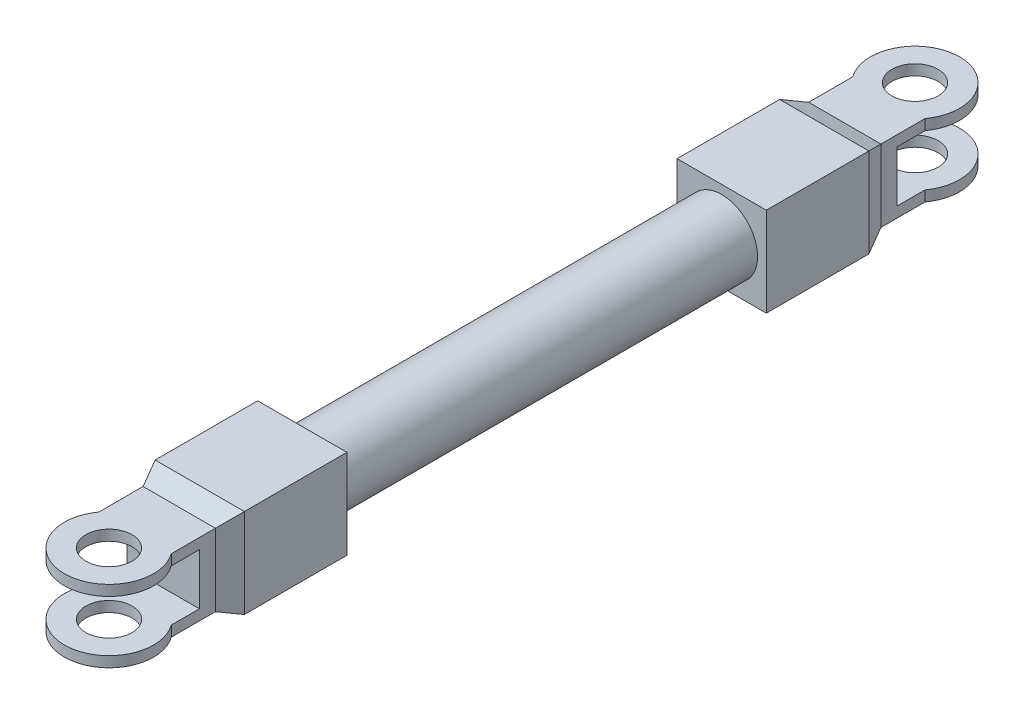
SolidWorks part; units mm, degrees
ref_plane "Front Plane" through (0, 0, 0) normal (0, 0, 1) x (1, 0, 0)
ref_plane "Top Plane" through (0, 0, 0) normal (0, 1, 0) x (1, 0, 0)
ref_plane "Right Plane" through (0, 0, 0) normal (1, 0, 0) x (0, 0, -1)
sketch "Sketch2" plane through (0, 0, 0) normal (0, 0, 1) x (1, 0, 0)
  circle A0 centre (0, 0) radius 70
  dimension "D1" = 140
extrude "Boss-Extrude2" add sketch "Sketch2" against normal blind 1018
sketch "Sketch4" plane through (0, 0, 0) normal (0, 0, 1) x (1, 0, 0)
  line L1 (-87, 87) -> (87, 87)
  line L2 (-87, 87) -> (-87, -87)
  line L3 (-87, -87) -> (87, -87)
  line L4 (87, 87) -> (87, -87)
  line L5 (-87, 87) -> (87, -87) construction
  line L6 (-87, -87) -> (87, 87) construction
  point P0 (0, 0)
  dimension "D1" = 174
  dimension "D2" = 174
extrude "Boss-Extrude3" add sketch "Sketch4" against normal mid plane 200
sketch "Sketch7" plane through (0, 0, -1018) normal (0, 0, -1) x (-1, 0, 0)
  line L1 (-87, 87) -> (87, 87)
  line L2 (-87, 87) -> (-87, -87)
  line L3 (-87, -87) -> (87, -87)
  line L4 (87, 87) -> (87, -87)
  line L5 (-87, 87) -> (87, -87) construction
  line L6 (-87, -87) -> (87, 87) construction
  point P0 (0, 0)
  dimension "D1" = 174
  dimension "D2" = 174
extrude "Boss-Extrude4" add sketch "Sketch7" against normal mid plane 200
ref_plane "Plane1" through (0, 0, 140) normal (0, 0, 1) x (1, 0, 0)
sketch "Sketch8" plane through (0, 0, 140) normal (0, 0, 1) x (1, 0, 0)
  line L1 (-70.5, 70.5) -> (70.5, 70.5)
  line L2 (-70.5, 70.5) -> (-70.5, -70.5)
  line L3 (-70.5, -70.5) -> (70.5, -70.5)
  line L4 (70.5, 70.5) -> (70.5, -70.5)
  line L5 (-70.5, 70.5) -> (70.5, -70.5) construction
  line L6 (-70.5, -70.5) -> (70.5, 70.5) construction
  point P0 (0, 0)
  dimension "D1" = 141
  dimension "D2" = 141
loft "Loft1" add profiles "Sketch8" section face at (0, 0, 100) section "Sketch8"
ref_plane "Plane2" through (0, 0, -160) normal (0, 0, -1) x (-1, 0, 0)
sketch "Sketch9" plane through (0, 0, -160) normal (0, 0, -1) x (-1, 0, 0)
  line L5 (-71.5, 71.5) -> (71.5, 71.5)
  line L6 (-71.5, 71.5) -> (-71.5, -71.5)
  line L7 (-71.5, -71.5) -> (71.5, -71.5)
  line L8 (71.5, 71.5) -> (71.5, -71.5)
  line L9 (-71.5, 71.5) -> (71.5, -71.5) construction
  line L10 (-71.5, -71.5) -> (71.5, 71.5) construction
  point P0 (0, 0)
  point P1 (0, 0)
  dimension "D1" = 143
  dimension "D2" = 143
ref_plane "Plane3" through (0, 0, -1158) normal (0, 0, -1) x (-1, 0, 0)
sketch "Sketch10" plane through (0, 0, -1158) normal (0, 0, -1) x (-1, 0, 0)
  line L0 (-71.5, 71.5) -> (71.5, -71.5) construction
  line L1 (-70.5, 70.5) -> (70.5, 70.5)
  line L2 (-70.5, 70.5) -> (-70.5, -70.5)
  line L3 (-70.5, -70.5) -> (70.5, -70.5)
  line L4 (70.5, 70.5) -> (70.5, -70.5)
  line L5 (-70.5, 70.5) -> (70.5, -70.5) construction
  line L6 (-70.5, -70.5) -> (70.5, 70.5) construction
  point P0 (0, 0)
  dimension "D1" = 141
  dimension "D2" = 141
loft "Loft8" add profiles "Sketch10" section face at (0, 0, -1118) section "Sketch10"
ref_plane "Plane4" through (0, 70.5, 0) normal (0, 1, 0) x (-1, 0, 0)
sketch "Sketch14" plane through (0, 70.5, 0) normal (0, 1, 0) x (-1, 0, 0)
  line L0 (94.8419, 140) -> (-94.8419, 140) construction
  circle A0 centre (0, 277) radius 87
  dimension "D1" = 174
  dimension "D2" = 137
extrude "Boss-Extrude5" add sketch "Sketch14" against normal blind 141 separate body contours A0
sketch "Sketch16" plane through (0, 70.5, 0) normal (0, 1, 0) x (1, 0, 0)
  circle A0 centre (0, -277) radius 45
  dimension "D1" = 90
extrude "Cut-Extrude1" cut sketch "Sketch16" against normal up to next (141 mm away)
sketch "Sketch17" plane through (0, 0, 140) normal (0, 0, 1) x (1, 0, 0)
  line L1 (-70.5, 70.5) -> (70.5, 70.5)
  line L2 (-70.5, 70.5) -> (-70.5, -70.5)
  line L3 (-70.5, -70.5) -> (70.5, -70.5)
  line L4 (70.5, 70.5) -> (70.5, -70.5)
  line L5 (-70.5, 70.5) -> (70.5, -70.5) construction
  line L6 (-70.5, -70.5) -> (70.5, 70.5) construction
  point P0 (0, 0)
  dimension "D1" = 141
  dimension "D2" = 141
extrude "Boss-Extrude6" add sketch "Sketch17" along normal up to next
ref_plane "Plane6" through (-94.5, 0, 0) normal (-1, 0, 0) x (0, 0, 1)
sketch "Sketch23" plane through (-94.5, 0, 0) normal (-1, 0, 0) x (0, 0, 1)
  line L0 (226.0221, -70.5) -> (364, -70.5) construction
  line L1 (171.1765, -50) -> (367.3984, -50)
  line L2 (171.1765, -50) -> (171.1765, 50)
  line L3 (171.1765, 50) -> (367.3984, 50)
  line L4 (367.3984, -50) -> (367.3984, 50)
  dimension "D1" = 100
  dimension "D2" = 20.5
extrude "Cut-Extrude2" cut sketch "Sketch23" against normal blind 201
sketch "Sketch24" plane through (0, 0, 0) normal (0, 1, 0) x (1, 0, 0)
  line L0 (-70.5, 1158) -> (70.5, 1158) construction
  line L2 (-70.5, 1158) -> (70.5, 1158)
  line L3 (-70.5, 1158) -> (-70.5, 1244.0221)
  line L5 (70.5, 1158) -> (70.5, 1244.0221)
  arc A0 (70.5, 1244.0221) -> (-70.5, 1244.0221) centre (0, 1295) ccw
  point P4 (0, 1158)
  dimension "D1" = 174
  dimension "D2" = 137
  dimension "D3" = 141
extrude "Boss-Extrude7" add sketch "Sketch24" along normal mid plane 141 separate body
sketch "Sketch26" plane through (0, 70.5, 0) normal (0, 1, 0) x (1, 0, 0)
  circle A0 centre (0, 1295) radius 45
  dimension "D1" = 90
sketch "Sketch27" plane through (0, -70.5, 0) normal (0, -1, 0) x (1, 0, 0)
  circle A0 centre (0, -1295) radius 45
  dimension "D1" = 90
extrude "Cut-Extrude3" cut sketch "Sketch26" against normal up to next (141 mm away) contours A0
ref_plane "Plane7" through (-100.5, 0, 0) normal (-1, 0, 0) x (0, 0, 1)
sketch "Sketch28" plane through (-100.5, 0, 0) normal (-1, 0, 0) x (0, 0, 1)
  line L0 (-1158, -70.5) -> (-1158, 70.5) construction
  line L1 (-1468.6898, 50) -> (-1189.18, 50)
  line L2 (-1468.6898, 50) -> (-1468.6898, -50)
  line L3 (-1468.6898, -50) -> (-1189.18, -50)
  line L4 (-1189.18, 50) -> (-1189.18, -50)
  line L5 (-1468.6898, 50) -> (-1189.18, -50) construction
  line L6 (-1468.6898, -50) -> (-1189.18, 50) construction
  line L7 (-1244.0221, 70.5) -> (-1382, 70.5) construction
  point P0 (-1328.9349, 0)
  dimension "D1" = 100
  dimension "D2" = 31.18
  dimension "D3" = 20.5
extrude "Cut-Extrude4" cut sketch "Sketch28" against normal up to next
sketch "Sketch29" plane through (0, 70.5, 0) normal (0, 1, 0) x (1, 0, 0)
  point P0 (0, -277)
sketch "Sketch30" plane through (0, -70.5, 0) normal (0, -1, 0) x (1, 0, 0)
  point P0 (0, 277)
